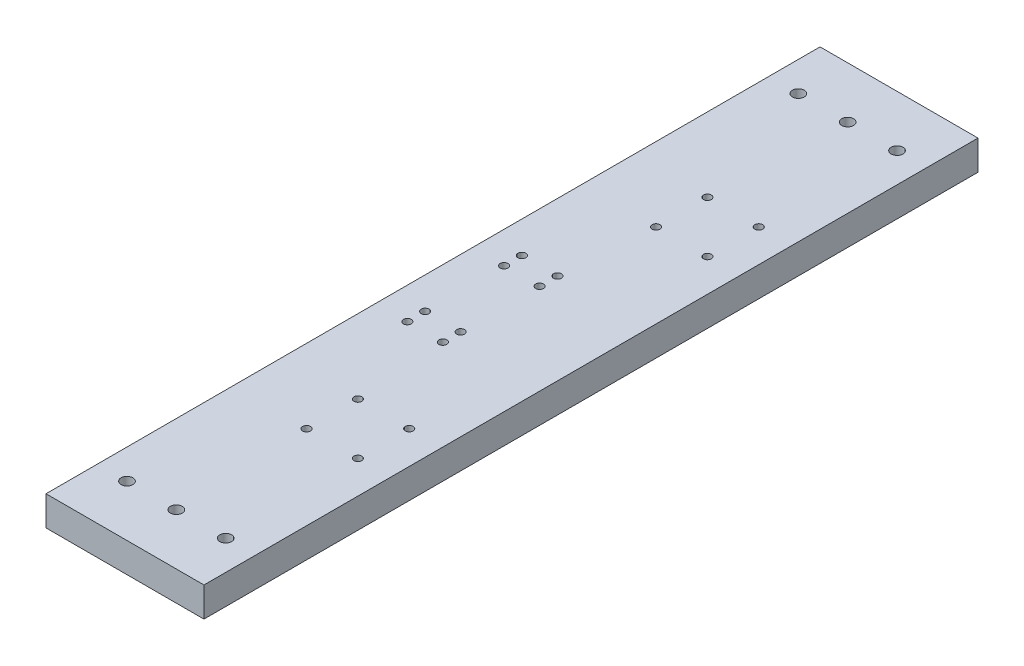
SolidWorks part; units mm, degrees
ref_plane "前视基准面" through (0, 0, 0) normal (0, 0, 1) x (1, 0, 0)
ref_plane "上视基准面" through (0, 0, 0) normal (0, 1, 0) x (1, 0, 0)
ref_plane "右视基准面" through (0, 0, 0) normal (1, 0, 0) x (0, 0, -1)
other "Configuration Table"
sketch "草图1" plane through (0, 0, 0) normal (0, 0, 1) x (1, 0, 0)
  line L1 (0, 0) -> (80, 0)
  line L2 (0, 0) -> (0, 15)
  line L3 (0, 15) -> (80, 15)
  line L4 (80, 0) -> (80, 15)
  dimension "D1" = 15
  dimension "D2" = 80
extrude "凸台-拉伸1" add sketch "草图1" along normal blind 392
sketch "草图2" plane through (0, 15, 0) normal (0, 1, 0) x (1, 0, 0)
  line L0 (80, -196) -> (-22.4055, -196) construction
  line L1 (80, -392) -> (80, 0) construction
  circle A0 centre (65, -26) radius 3
  circle A1 centre (40, -26) radius 3
  circle A2 centre (15, -26) radius 3
  circle A3 centre (15, -366) radius 3
  circle A4 centre (40, -366) radius 3
  circle A5 centre (65, -366) radius 3
  dimension "D1" = 6
extrude "切除-拉伸1" cut sketch "草图2" against normal through all
sketch "草图3" plane through (0, 0, 0) normal (0, -1, 0) x (-1, 0, 0)
  line L0 (-80, -196) -> (0, -196) construction
  line L1 (-80, -392) -> (-80, 0) construction
  line L2 (0, -392) -> (0, 0) construction
  circle A0 centre (-34, -216) radius 2
  circle A1 centre (-34, -225) radius 2
  circle A2 centre (-16, -225) radius 2
  circle A3 centre (-16, -216) radius 2
  circle A4 centre (-16, -176) radius 2
  circle A5 centre (-16, -167) radius 2
  circle A6 centre (-34, -167) radius 2
  circle A7 centre (-34, -176) radius 2
  point P26 (-29.6411, -225)
  point P27 (-34, -225)
  point P28 (-16, -225)
  dimension "D1" = 4
  dimension "D2" = 4
  dimension "D3" = 4
  dimension "D4" = 4
extrude "切除-拉伸2" cut sketch "草图3" against normal through all
sketch "草图4" plane through (0, 15, 0) normal (0, 1, 0) x (1, 0, 0)
  line L0 (80, -196) -> (-5.0808, -196) construction
  line L1 (80, -392) -> (80, 0) construction
  circle A0 centre (63.45, -94.5) radius 2
  circle A1 centre (37.45, -94.5) radius 2
  circle A2 centre (37.45, -120.5) radius 2
  circle A3 centre (63.45, -120.5) radius 2
  circle A4 centre (63.45, -271.5) radius 2
  circle A5 centre (37.45, -271.5) radius 2
  circle A6 centre (37.45, -297.5) radius 2
  circle A7 centre (63.45, -297.5) radius 2
  dimension "D1" = 4
extrude "切除-拉伸3" cut sketch "草图4" against normal through all
